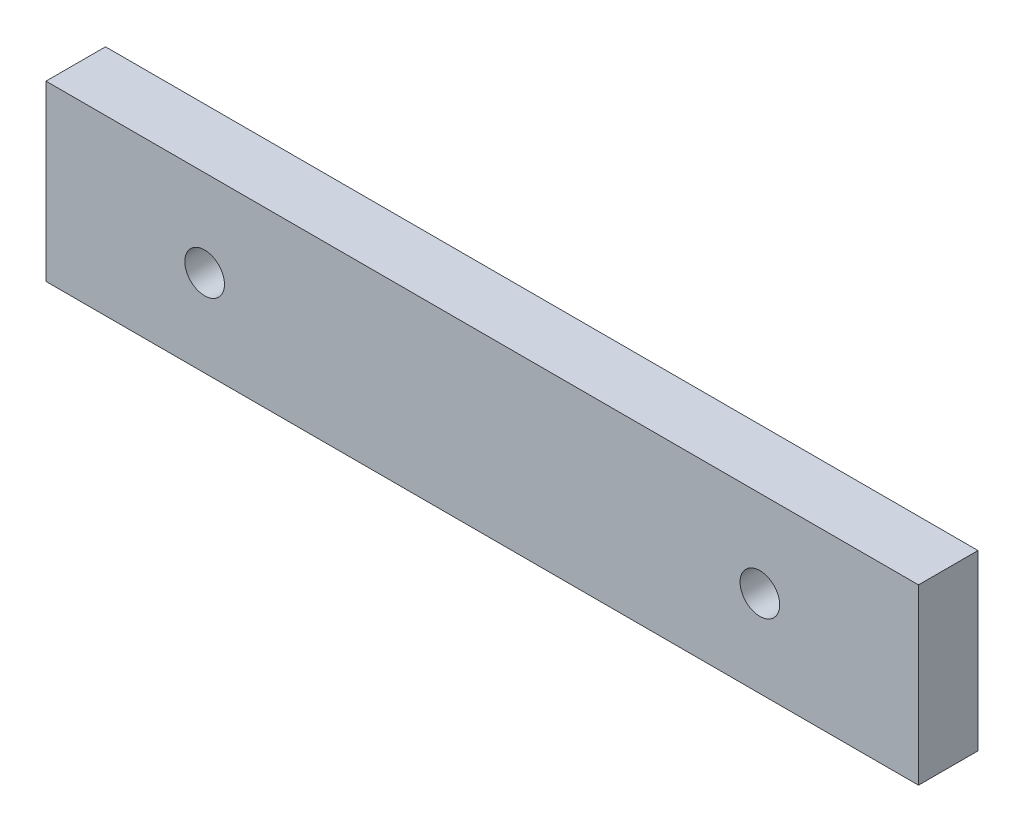
SolidWorks part; units mm, degrees
ref_plane "Front Plane" through (0, 0, 0) normal (0, 0, 1) x (1, 0, 0)
ref_plane "Top Plane" through (0, 0, 0) normal (0, 1, 0) x (1, 0, 0)
ref_plane "Right Plane" through (0, 0, 0) normal (1, 0, 0) x (0, 0, -1)
sketch "Sketch1" plane through (0, 0, 0) normal (0, 0, 1) x (1, 0, 0)
  line L1 (-88, 17.5) -> (88, 17.5)
  line L2 (-88, 17.5) -> (-88, -17.5)
  line L3 (-88, -17.5) -> (88, -17.5)
  line L4 (88, 17.5) -> (88, -17.5)
  line L5 (-88, 17.5) -> (88, -17.5) construction
  line L6 (-88, -17.5) -> (88, 17.5) construction
  circle A0 centre (-56, 0) radius 4
  circle A2 centre (56, 0) radius 4
  point P0 (0, 0)
  dimension "D1" = 176
  dimension "D2" = 35
extrude "Boss-Extrude1" add sketch "Sketch1" along normal blind 12
